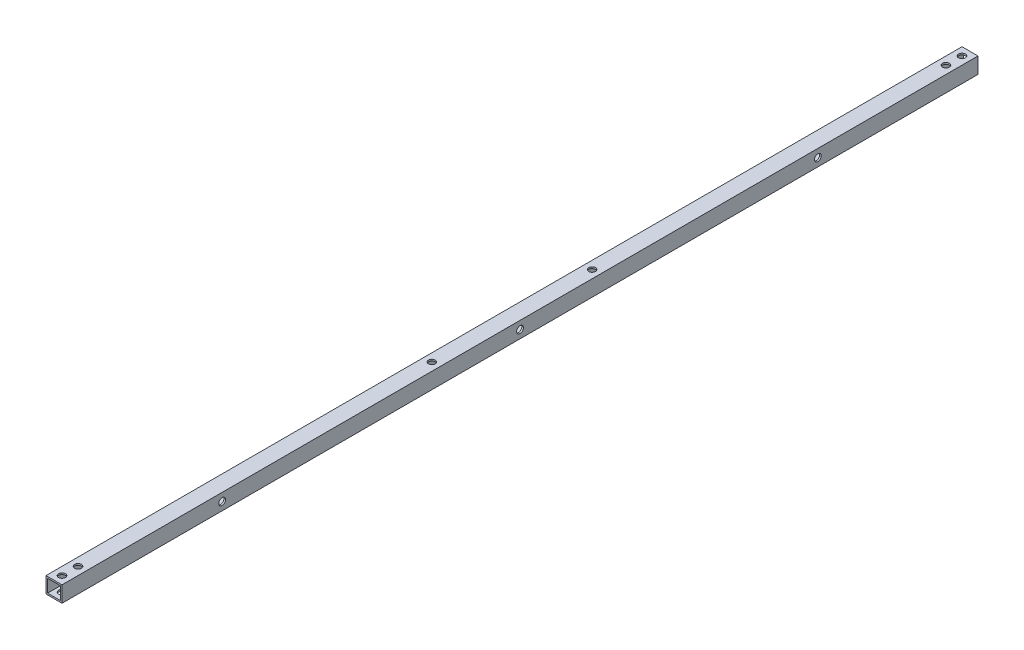
SolidWorks part; units mm, degrees
ref_plane "Front Plane" through (0, 0, 0) normal (0, 0, 1) x (1, 0, 0)
ref_plane "Top Plane" through (0, 0, 0) normal (0, 1, 0) x (1, 0, 0)
ref_plane "Right Plane" through (0, 0, 0) normal (1, 0, 0) x (0, 0, -1)
sketch "Sketch1" plane through (0, 0, 0) normal (0, 0, 1) x (1, 0, 0)
  line L1 (0, 0) -> (10, 0)
  line L2 (0, 0) -> (0, 10)
  line L3 (0, 10) -> (10, 10)
  line L4 (10, 0) -> (10, 10)
  line L5 (1, 9) -> (9, 9)
  line L6 (1, 9) -> (1, 1)
  line L7 (1, 1) -> (9, 1)
  line L8 (9, 9) -> (9, 1)
  dimension "D1" = 10
  dimension "D2" = 10
  dimension "D3" = 8
  dimension "D4" = 8
  dimension "D5" = 1
  dimension "D6" = 1
extrude "Boss-Extrude1" add sketch "Sketch1" along normal blind 572
sketch "Sketch2" plane through (0, 10, 0) normal (0, 1, 0) x (1, 0, 0)
  line L0 (10, 0) -> (0, 0) construction
  line L1 (10, -572) -> (10, 0) construction
  line L2 (0, -572) -> (0, 0) construction
  line L4 (10, -572) -> (0, -572) construction
  circle A0 centre (5, -5) radius 2.125
  circle A1 centre (5, -15) radius 2.125
  circle A2 centre (5, -557) radius 2.125
  circle A3 centre (5, -567) radius 2.125
  dimension "D1" = 4.25
  dimension "D2" = 4.25
  dimension "D7" = 4.25
  dimension "D8" = 4.25
  dimension "D9" = 5
  dimension "D10" = 5
  dimension "D11" = 15
  dimension "D12" = 5
  dimension "D3" = 5
  dimension "D4" = 15
  dimension "D5" = 5
  dimension "D6" = 5
extrude "Cut-Extrude1" cut sketch "Sketch2" against normal blind 116
sketch "Sketch3" plane through (0, 0, 0) normal (0, -1, 0) x (1, 0, 0)
  line L0 (10, 572) -> (10, 0) construction
  line L1 (0, 0) -> (10, 0) construction
  line L2 (0, 572) -> (10, 572) construction
  circle A0 centre (5, 336) radius 2.1
  circle A1 centre (5, 236) radius 2.125
  dimension "D1" = 4.25
  dimension "D2" = 5
  dimension "D3" = 236
  dimension "4.25" = 4.2
  dimension "D5" = 5
  dimension "D6" = 236
extrude "Cut-Extrude2" cut sketch "Sketch3" against normal blind 10
sketch "Sketch5" plane through (10, 0, 0) normal (1, 0, 0) x (0, 0, -1)
  line L0 (0, 0) -> (0, 10) construction
  line L1 (-572, 0) -> (-572, 10) construction
  line L2 (-572, 0) -> (0, 0) construction
  circle A0 centre (-472, 5) radius 2.125
  circle A1 centre (-100, 5) radius 2.125
  circle A2 centre (-286, 5) radius 2.125
  dimension "D1" = 4.25
  dimension "D2" = 4.25
  dimension "D3" = 4.25
  dimension "D4" = 100
  dimension "D5" = 100
  dimension "D6" = 286
  dimension "D7" = 5
extrude "Cut-Extrude3" cut sketch "Sketch5" against normal blind 10
